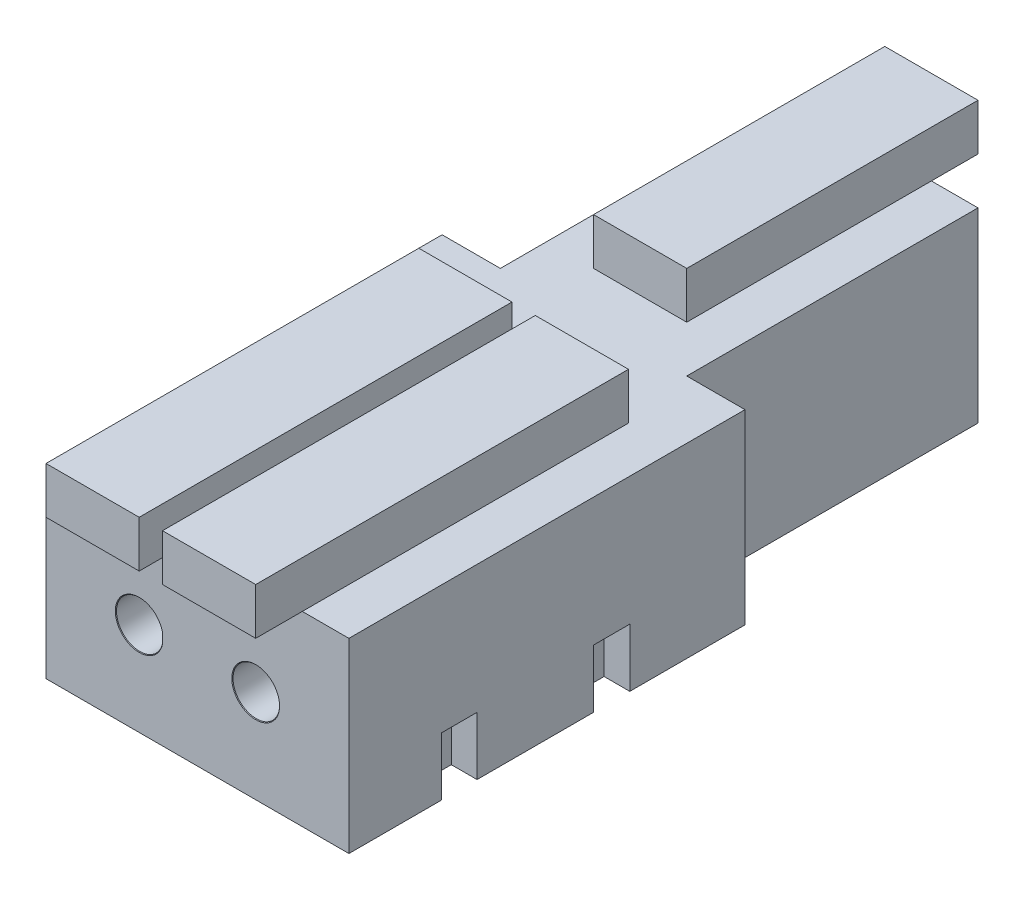
SolidWorks part; units mm, degrees
material "ABS"
ref_plane "Front Plane" through (0, 0, 0) normal (0, 0, 1) x (1, 0, 0)
ref_plane "Top Plane" through (0, 0, 0) normal (0, 1, 0) x (1, 0, 0)
ref_plane "Right Plane" through (0, 0, 0) normal (1, 0, 0) x (0, 0, -1)
sketch "Sketch1" plane through (0, 0, 0) normal (0, 1, 0) x (1, 0, 0)
  line L1 (0, 0) -> (8, 0)
  line L2 (0, 0) -> (0, 17)
  line L3 (0, 17) -> (8, 17)
  line L4 (8, 0) -> (8, 17)
  dimension "D1" = 8
  dimension "D2" = 17
extrude "connector_body" add sketch "Sketch1" along normal blind 8
sketch "Sketch2" plane through (0, 0, 0) normal (0, 0, -1) x (-1, 0, 0)
  line L0 (0, 8) -> (0, 0) construction
  line L1 (-8, 8) -> (0, 8) construction
  point P0 (-4, 4)
  dimension "D1" = 4
  dimension "D2" = 4
hole_wizard "cable_hole" positions "Sketch2" profile "Sketch3" hole size "Ø2.0" standard "DIN"
sketch "Sketch3" plane through (4, 4, 0) normal (1, 0, 0) x (0, -1, 0)
  line L0 (0, 0) -> (0, 10.6009)
  line L1 (0, 10.6009) -> (1, 10)
  line L2 (1, 10) -> (1, 0.025)
  line L3 (1, 0.025) -> (1.025, 0)
  line L5 (1.025, 0) -> (0, 0)
  line L6 (-1, 0.025) -> (-1.025, 0) construction
  line L10 (0, 10.6009) -> (-1, 10) construction
  line L11 (0, -6.35) -> (0, 107.95) construction
  dimension "Hole Dia." = 2
  dimension "Hole Depth" = 10
  dimension "Near C'Sink Dia." = 2.05
  dimension "Near C'Sink Angle" = 90
  dimension "Drill Angle" = 118
sketch "Sketch4" plane through (0, 8, 0) normal (0, 1, 0) x (1, 0, 0)
  line L0 (8, 0) -> (8, 17) construction
  line L1 (2, 14) -> (6, 14)
  line L2 (2, 14) -> (2, -2)
  line L3 (2, -2) -> (6, -2)
  line L4 (6, 14) -> (6, -2)
  line L6 (8, 17) -> (0, 17) construction
  dimension "D1" = 4
  dimension "D2" = 2
  dimension "D3" = 3
  dimension "D4" = 16
extrude "clamp" add sketch "Sketch4" along normal blind 2
pattern_linear "connector_pattern" count 2 spacing 5 along (1, 0, 0) of "connector_body", "cable_hole", "clamp"
sketch "Sketch5" plane through (0, 8, 0) normal (0, 1, 0) x (1, 0, 0)
  line L0 (13, 17) -> (0, 17) construction
  line L1 (2.5, 17) -> (10.5, 17)
  line L2 (2.5, 17) -> (2.5, 29.5)
  line L3 (2.5, 29.5) -> (10.5, 29.5)
  line L4 (10.5, 17) -> (10.5, 29.5)
  line L5 (0, 17) -> (0, 0) construction
  dimension "D1" = 8
  dimension "D2" = 2.5
  dimension "D3" = 12.5
extrude "single_body" add sketch "Sketch5" against normal up to vertex (8 mm away)
sketch "Sketch6" plane through (0, 0, 0) normal (-1, 0, 0) x (0, 0, 1)
  line L0 (-17, 0) -> (0, 0) construction
  line L1 (-12, 0) -> (-10.5, 0)
  line L2 (-12, 0) -> (-12, 2.5004)
  line L3 (-12, 2.5004) -> (-10.5, 2.5004)
  line L4 (-10.5, 0) -> (-10.5, 2.5004)
  line L5 (-17, 0) -> (-17, 8) construction
  line L6 (-5.5, 0) -> (-4, 0)
  line L7 (-5.5, 0) -> (-5.5, 2.5004)
  line L8 (-5.5, 2.5004) -> (-4, 2.5004)
  line L9 (-4, 0) -> (-4, 2.5004)
  point P12 (-4.75, 0)
  dimension "D1" = 5
  dimension "D2" = 1.5
  dimension "D3" = 1.5
  dimension "D4" = 2.5004
  dimension "D5" = 5
extrude "chaining_nobs" add sketch "Sketch6" along normal blind 1
sketch "Sketch7" plane through (0, 0, 0) normal (0, -1, 0) x (1, 0, 0)
  line L0 (13, 0) -> (13, -17) construction
  line L1 (13, -3.9813) -> (11.8964, -3.9813)
  line L2 (13, -3.9813) -> (13, -5.5)
  line L3 (13, -5.5) -> (11.8964, -5.5)
  line L4 (11.8964, -3.9813) -> (11.8964, -5.5)
  line L5 (-1, -10.5) -> (0, -10.5) construction
  line L6 (11.8964, -12.0562) -> (13, -12.0562)
  line L7 (11.8964, -12.0562) -> (11.8964, -10.5)
  line L8 (11.8964, -10.5) -> (13, -10.5)
  line L9 (13, -12.0562) -> (13, -10.5)
extrude "chaining_nobs_cutout" cut sketch "Sketch7" against normal blind 2.5
sketch "Sketch8" plane through (0, 8, 0) normal (0, 1, 0) x (1, 0, 0)
  line L0 (2.5, 29.5) -> (2.5, 17) construction
  line L1 (4.5, 19) -> (8.5, 19)
  line L2 (4.5, 19) -> (4.5, 31.5)
  line L3 (4.5, 31.5) -> (8.5, 31.5)
  line L4 (8.5, 19) -> (8.5, 31.5)
  line L5 (13, 17) -> (10.5, 17) construction
  line L6 (10.5, 29.5) -> (2.5, 29.5) construction
  dimension "D1" = 4
  dimension "D2" = 2
  dimension "D3" = 2
  dimension "D4" = 2
extrude "single_body_clamp" add sketch "Sketch8" along normal up to vertex (2 mm away)
